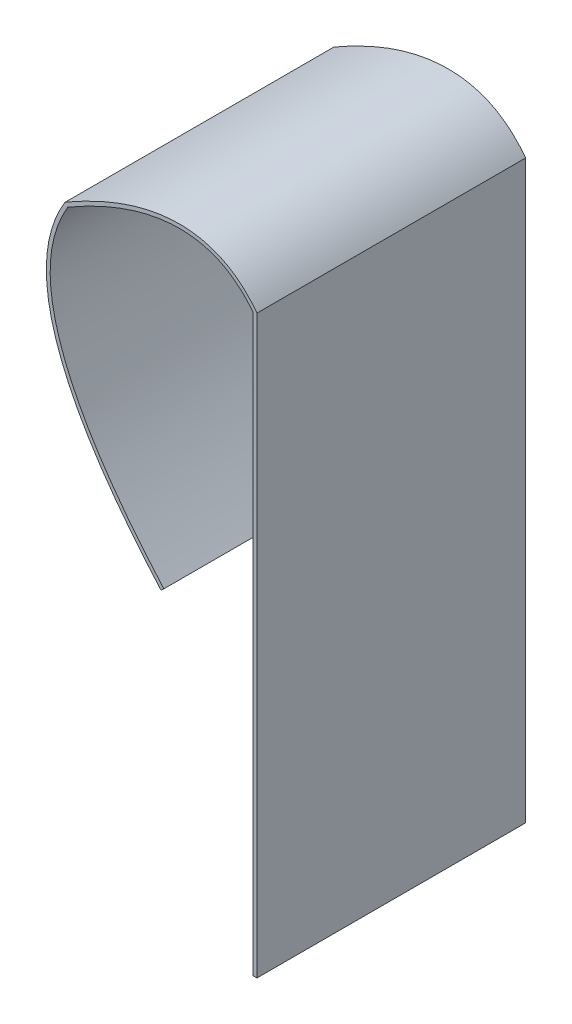
SolidWorks part; units mm, degrees
ref_plane "Front Plane" through (0, 0, 0) normal (0, 0, 1) x (1, 0, 0)
ref_plane "Top Plane" through (0, 0, 0) normal (0, 1, 0) x (1, 0, 0)
ref_plane "Right Plane" through (0, 0, 0) normal (1, 0, 0) x (0, 0, -1)
sketch "Sketch1" plane through (0, 0, 0) normal (0, 0, 1) x (1, 0, 0)
  line L0 (2.4, 7.4663) -> (2.4, -7.5)
  line L1 (2.4, -7.5) -> (2.5, -7.5)
  line L2 (0, 0) -> (0.0749, 0.0663)
  line L4 (2.5, 7.5) -> (2.5, -7.5)
  spline S0 degree 2 poles (0, 0) (-4.1912, 4.7312) (-2.5, 7.5) knots 0 0 0 1 1 1
  spline S1 degree 1 poles (0.0749, 0.0663) (-2.4277, 7.4264) knots 0 0 1 1 construction
  spline S2 degree 3 poles (-2.5, 7.5) (0.7321, 9.3881) (2.0126, 8.1482) (2.5, 7.5) knots 0 0 0 0 0.389138 0.389138 0.389138 0.389138
  spline S3 degree 1 poles (-2.4277, 7.4264) (2.4, 7.4663) knots 0 0 1 1 construction
  spline S4 degree 3 poles (0.0749, 0.0663) (-0.0938, 0.2567) (-0.4318, 0.6503) (-1.03, 1.3978) (-1.6693, 2.2996) (-2.2511, 3.3156) (-2.784, 4.5867) (-3.0002, 6.0044) (-2.6898, 6.9899) (-2.4277, 7.4264) knots 0 0 0 0 0.062251 0.124502 0.249004 0.373506 0.498008 0.747012 0.996016 0.996016 0.996016 0.996016
  spline S5 degree 3 poles (-2.4277, 7.4264) (-2.2415, 7.5346) (-1.8482, 7.7484) (-1.1573, 8.0665) (-0.3856, 8.3211) (0.3793, 8.4255) (1.2131, 8.3599) (1.7949, 8.0751) (2.1979, 7.7146) (2.332, 7.5549) (2.4, 7.4663) knots 0.000887 0.000887 0.000887 0.000887 0.024817 0.048746 0.096605 0.144464 0.192323 0.28804 0.335899 0.383758 0.383758 0.383758 0.383758
  point P0 (0, 0)
  dimension "D1" = 15
  dimension "D2" = 5
  dimension "D3" = 0.1
extrude "Boss-Extrude1" add sketch "Sketch1" along normal mid plane 7
